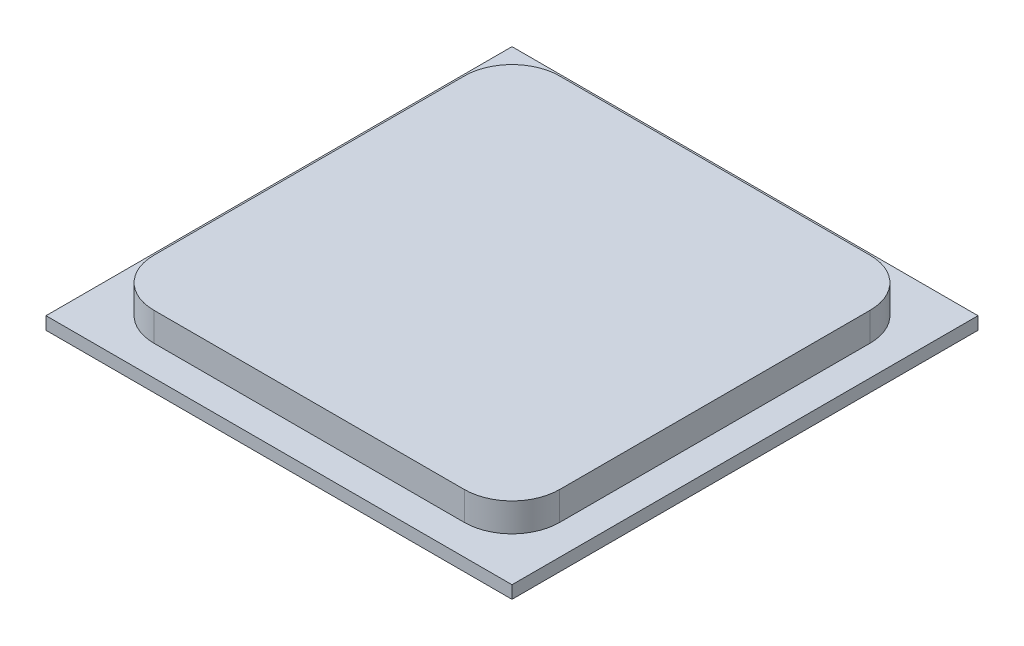
SolidWorks part; units mm, degrees
ref_plane "前视基准面" through (0, 0, 0) normal (0, 0, 1) x (1, 0, 0)
ref_plane "上视基准面" through (0, 0, 0) normal (0, 1, 0) x (1, 0, 0)
ref_plane "右视基准面" through (0, 0, 0) normal (1, 0, 0) x (0, 0, -1)
sketch "草图1" plane through (0, 0, 0) normal (0, 1, 0) x (1, 0, 0)
  line L1 (73.5, -73.5) -> (-73.5, -73.5)
  line L2 (73.5, -73.5) -> (73.5, 73.5)
  line L3 (73.5, 73.5) -> (-73.5, 73.5)
  line L4 (-73.5, -73.5) -> (-73.5, 73.5)
  line L5 (73.5, -73.5) -> (-73.5, 73.5) construction
  line L6 (73.5, 73.5) -> (-73.5, -73.5) construction
  point P0 (0, 0)
  dimension "D1" = 147
  dimension "D2" = 147
extrude "凸台-拉伸1" add sketch "草图1" along normal blind 4
sketch "草图2" plane through (0, 4, 0) normal (0, 1, 0) x (1, 0, 0)
  line L1 (49, -64) -> (-49, -64)
  line L2 (64, -49) -> (64, 49)
  line L3 (49, 64) -> (-49, 64)
  line L4 (-64, -49) -> (-64, 49)
  line L5 (64, -64) -> (-64, 64) construction
  line L6 (64, 64) -> (-64, -64) construction
  arc A0 (-49, -64) -> (-64, -49) centre (-49, -49) cw
  arc A1 (49, -64) -> (64, -49) centre (49, -49) ccw
  arc A2 (64, 49) -> (49, 64) centre (49, 49) ccw
  arc A3 (-49, 64) -> (-64, 49) centre (-49, 49) ccw
  point P0 (0, 0)
  dimension "D3" = 15
  dimension "D1" = 128
  dimension "D2" = 128
extrude "凸台-拉伸2" add sketch "草图2" along normal blind 9
sketch "草图3" plane through (0, 0, 0) normal (0, -1, 0) x (1, 0, 0)
  line L1 (51.5, -51.5) -> (-51.5, -51.5)
  line L2 (51.5, -51.5) -> (51.5, 51.5)
  line L3 (51.5, 51.5) -> (-51.5, 51.5)
  line L4 (-51.5, -51.5) -> (-51.5, 51.5)
  line L5 (51.5, -51.5) -> (-51.5, 51.5) construction
  line L6 (51.5, 51.5) -> (-51.5, -51.5) construction
  point P0 (0, 0)
  dimension "D1" = 103
  dimension "D2" = 103
extrude "切除-拉伸1" cut sketch "草图3" against normal blind 1
